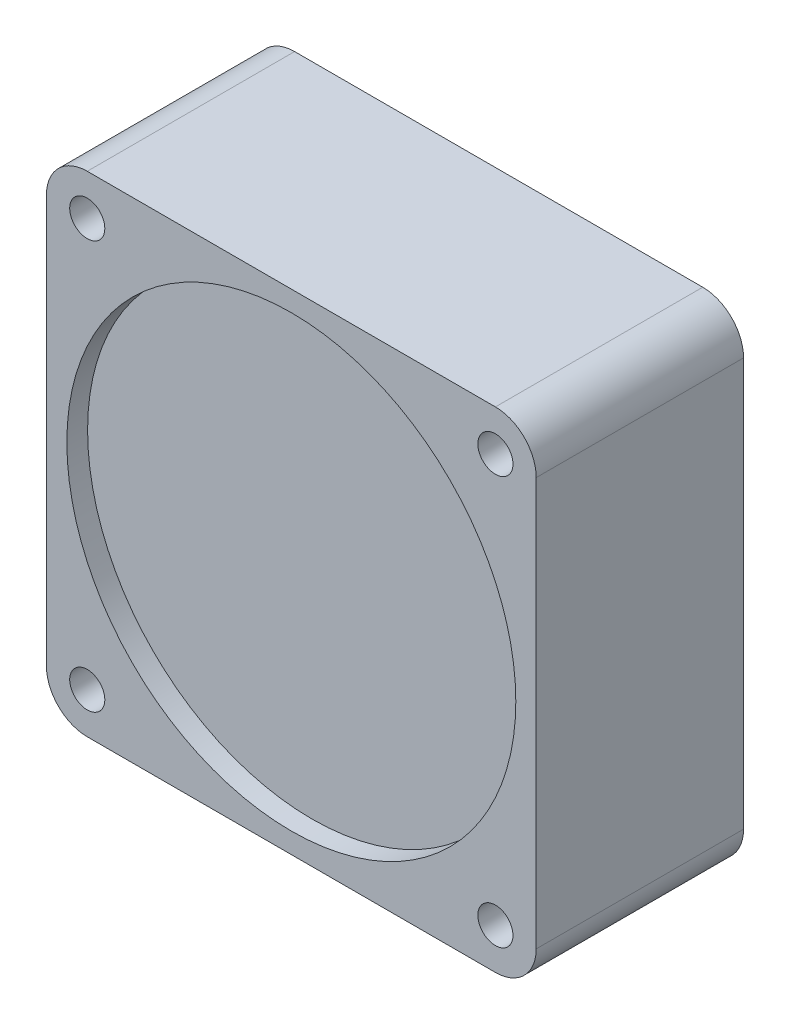
SolidWorks part; units mm, degrees
material "PA Type 6"
ref_plane "Front Plane" through (0, 0, 0) normal (0, 0, 1) x (1, 0, 0)
ref_plane "Top Plane" through (0, 0, 0) normal (0, 1, 0) x (1, 0, 0)
ref_plane "Right Plane" through (0, 0, 0) normal (1, 0, 0) x (0, 0, -1)
sketch "Sketch1" plane through (0, 0, 0) normal (0, 0, 1) x (1, 0, 0)
  line L1 (-30, 30) -> (30, 30)
  line L2 (-30, 30) -> (-30, -30)
  line L3 (-30, -30) -> (30, -30)
  line L4 (30, 30) -> (30, -30)
  line L5 (-30, 30) -> (30, -30) construction
  line L6 (-30, -30) -> (30, 30) construction
  line L7 (-25, 25) -> (25, 25) construction
  line L8 (-25, 25) -> (-25, -25) construction
  line L9 (-25, -25) -> (25, -25) construction
  line L10 (25, 25) -> (25, -25) construction
  line L11 (-25, 25) -> (25, -25) construction
  line L12 (-25, -25) -> (25, 25) construction
  circle A0 centre (-25, 25) radius 2.15
  circle A1 centre (25, 25) radius 2.15
  circle A2 centre (25, -25) radius 2.15
  circle A3 centre (-25, -25) radius 2.15
  arc A4 (-30, 25) -> (-25, 30) centre (-25, 25) cw
  arc A5 (30, 25) -> (25, 30) centre (25, 25) ccw
  arc A6 (-30, -25) -> (-25, -30) centre (-25, -25) ccw
  arc A7 (25, -30) -> (30, -25) centre (25, -25) ccw
  point P0 (0, 0)
  point P5 (0, 0)
  dimension "D5" = 4.3
  dimension "D1" = 60
  dimension "D2" = 60
  dimension "D3" = 50
  dimension "D4" = 50
extrude "Boss-Extrude1" add sketch "Sketch1" along normal blind 25.4 contours L3 A7 L4 A5 L1 A4 L2 A6 A3 A2 A1 A0
sketch "Sketch2" plane through (0, 0, 25.4) normal (0, 0, 1) x (1, 0, 0)
  circle A0 centre (0, 0) radius 27.5
  dimension "D1" = 55
extrude "Cut-Extrude1" cut sketch "Sketch2" against normal blind 2.54
